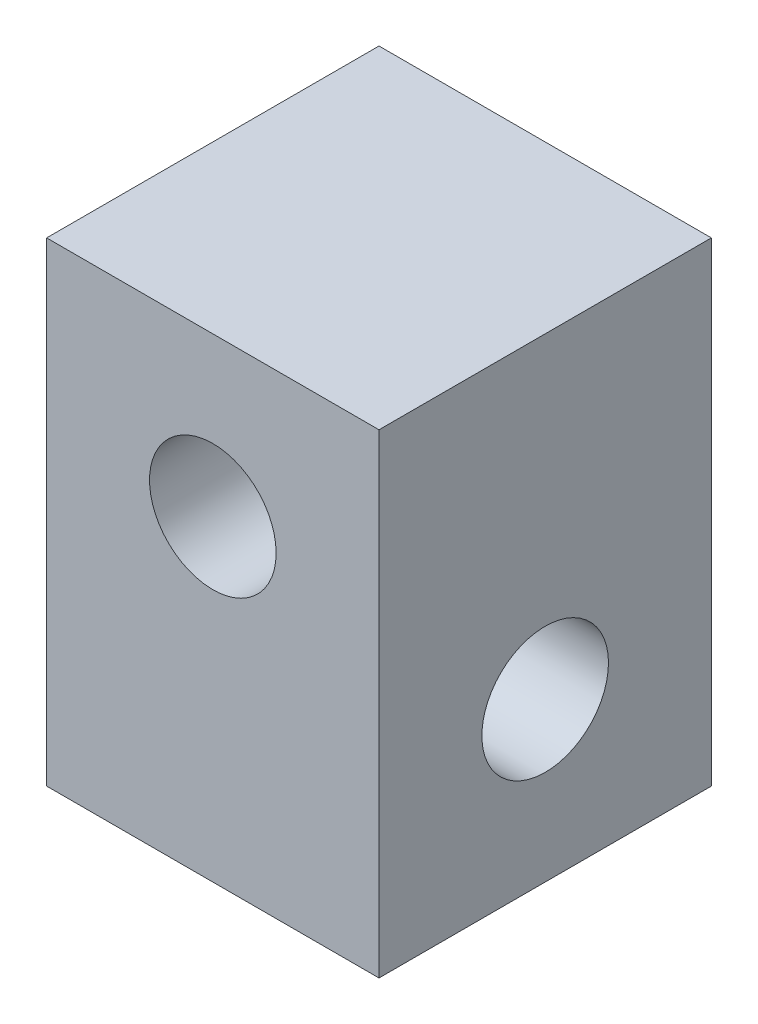
SolidWorks part; units mm, degrees
ref_plane "Front Plane" through (0, 0, 0) normal (0, 0, 1) x (1, 0, 0)
ref_plane "Top Plane" through (0, 0, 0) normal (0, 1, 0) x (1, 0, 0)
ref_plane "Right Plane" through (0, 0, 0) normal (1, 0, 0) x (0, 0, -1)
sketch "Sketch1" plane through (0, 0, 0) normal (0, 1, 0) x (1, 0, 0)
  line L1 (-10.5, -10.5) -> (10.5, -10.5)
  line L2 (-10.5, -10.5) -> (-10.5, 10.5)
  line L3 (-10.5, 10.5) -> (10.5, 10.5)
  line L4 (10.5, -10.5) -> (10.5, 10.5)
  line L5 (-10.5, -10.5) -> (10.5, 10.5) construction
  line L6 (-10.5, 10.5) -> (10.5, -10.5) construction
  point P0 (0, 0)
  dimension "D1" = 21
  dimension "D2" = 21
extrude "Boss-Extrude1" add sketch "Sketch1" along normal blind 30
sketch "Sketch2" plane through (0, 0, 10.5) normal (0, 0, 1) x (1, 0, 0)
  line L0 (-10.5, 30) -> (10.5, 30) construction
  circle A0 centre (0, 20) radius 4
  dimension "D1" = 8
  dimension "D2" = 10
extrude "Cut-Extrude1" cut sketch "Sketch2" against normal through all
sketch "Sketch3" plane through (10.5, 0, 0) normal (1, 0, 0) x (0, 0, -1)
  circle A0 centre (0, 10) radius 4
  dimension "D1" = 8
  dimension "D2" = 10
extrude "Cut-Extrude2" cut sketch "Sketch3" against normal through all
ref_plane "Plane1" through (0, 0, 0) normal (0.7071, 0, 0.7071) x (0.7071, 0, -0.7071)
